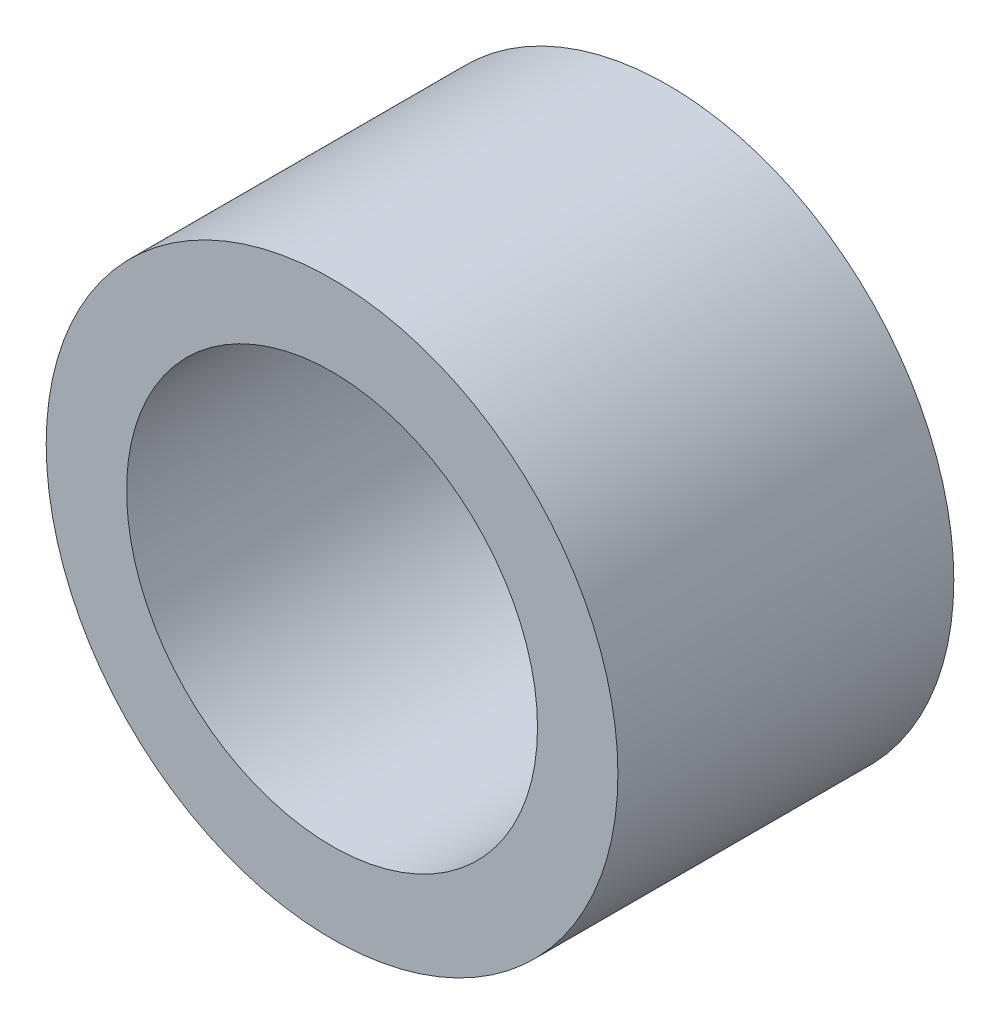
SolidWorks part; units mm, degrees
ref_plane "Front Plane" through (0, 0, 0) normal (0, 0, 1) x (1, 0, 0)
ref_plane "Top Plane" through (0, 0, 0) normal (0, 1, 0) x (1, 0, 0)
ref_plane "Right Plane" through (0, 0, 0) normal (1, 0, 0) x (0, 0, -1)
sketch "Sketch2" plane through (0, 0, 0) normal (0, 0, 1) x (1, 0, 0)
  circle A0 centre (0, 0) radius 57.5
  circle A1 centre (0, 0) radius 80
  dimension "D1" = 160
  dimension "D2" = 115
extrude "Boss-Extrude1" add sketch "Sketch2" along normal blind 64 and the other way blind 30
